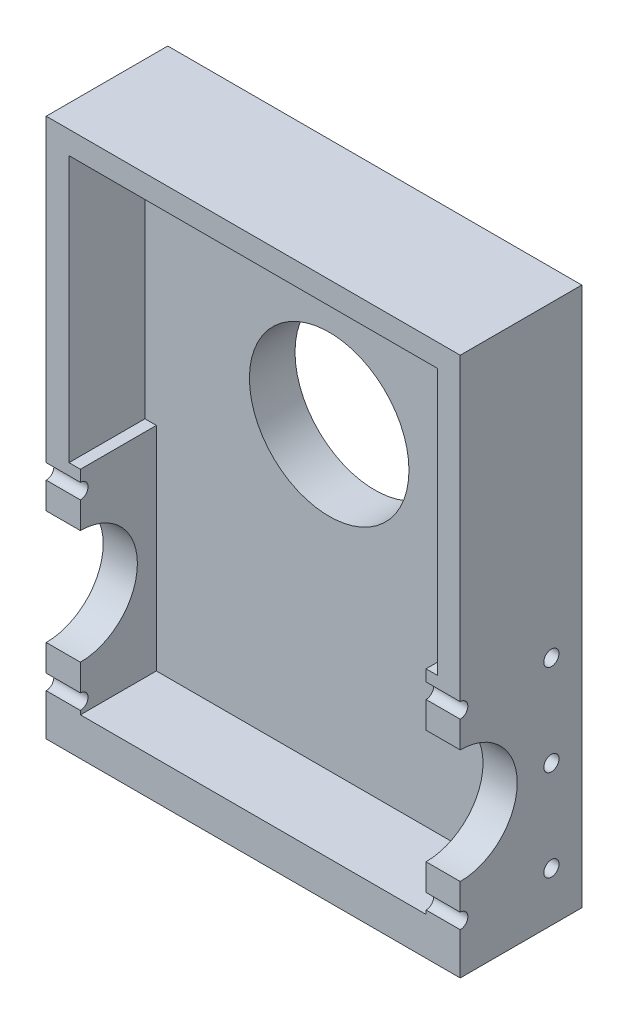
SolidWorks part; units mm, degrees
ref_plane "Front Plane" through (0, 0, 0) normal (0, 0, 1) x (1, 0, 0)
ref_plane "Top Plane" through (0, 0, 0) normal (0, 1, 0) x (1, 0, 0)
ref_plane "Right Plane" through (0, 0, 0) normal (1, 0, 0) x (0, 0, -1)
sketch "Sketch1" plane through (0, 0, 0) normal (0, 0, 1) x (1, 0, 0)
  line L0 (0, 0) -> (0, -52) construction
  line L2 (-48.5, -65) -> (48.5, -65)
  line L3 (-48.5, -65) -> (-48.5, 65)
  line L4 (-48.5, 65) -> (48.5, 65)
  line L5 (48.5, -65) -> (48.5, 65)
  line L6 (-48.5, -65) -> (48.5, 65) construction
  line L7 (-48.5, 65) -> (48.5, -65) construction
  dimension "D1" = 52
  dimension "D2" = 130
  dimension "D3" = 97
extrude "Boss-Extrude1" add sketch "Sketch1" along normal blind 12
sketch "Sketch8" plane through (0, 0, 12) normal (0, 0, 1) x (1, 0, 0)
  line L0 (0, 65) -> (0, 18) construction
  line L1 (48.5, 65) -> (-48.5, 65) construction
  circle A0 centre (0, 18) radius 43.5
  dimension "D2" = 87
  dimension "D1" = 47
sketch "Sketch9" plane through (0, 0, 12) normal (0, 0, 1) x (1, 0, 0)
  circle A0 centre (0, 18) radius 32
  point P19 (8.6603, 13)
  point P21 (0, 18)
  dimension "D1" = 64
extrude "Cut-Extrude2" cut sketch "Sketch9" against normal blind 12
sketch "Sketch11" plane through (0, 0, 0) normal (0, 0, 1) x (1, 0, 0)
  line L0 (-54.5, 71) -> (54.5, 71)
  line L1 (-48.5, -65) -> (48.5, -65)
  line L2 (-48.5, -65) -> (-48.5, 65)
  line L3 (-48.5, 65) -> (48.5, 65)
  line L4 (48.5, -65) -> (48.5, 65)
  line L5 (-48.5, -65) -> (48.5, 65) construction
  line L6 (-48.5, 65) -> (48.5, -65) construction
  line L7 (54.5, -71) -> (54.5, 71)
  line L8 (-54.5, -71) -> (54.5, -71)
  line L9 (-54.5, -71) -> (-54.5, 71)
  point P0 (0, 0)
  dimension "D1" = 6
extrude "Boss-Extrude4" add sketch "Sketch11" along normal blind 32
sketch "Sketch14" plane through (-54.5, 0, 0) normal (-1, 0, 0) x (0, 0, 1)
  line L0 (32, 71) -> (32, -71) construction
  line L1 (32, -71) -> (0, -71) construction
  circle A0 centre (32, -34) radius 15
  point P20 (32, -34)
  point P21 (34.6699, -46.5)
  point P22 (35.5, -27.9378)
  dimension "D1" = 30
  dimension "D2" = 37
sketch "Sketch18" plane through (-48.5, 0, 0) normal (1, 0, 0) x (0, 0, -1)
  line L0 (-12, 65) -> (-12, -65) construction
  line L1 (-32, -65) -> (-12, -65)
  line L2 (-32, -65) -> (-32, -5)
  line L3 (-32, -5) -> (-12, -5)
  line L4 (-12, -65) -> (-12, -5)
  dimension "D1" = 60
extrude "Boss-Extrude5" add sketch "Sketch18" along normal blind 3
mirror "Mirror1" about plane through (0, 0, 0) normal (1, 0, 0) of "Boss-Extrude5"
extrude "Cut-Extrude5" cut sketch "Sketch14" against normal through all
sketch "Sketch20" plane through (0, -65, 0) normal (0, 1, 0) x (1, 0, 0)
  line L1 (-45.5, -12) -> (45.5, -12)
  line L2 (-45.5, -12) -> (-45.5, -32)
  line L3 (-45.5, -32) -> (45.5, -32)
  line L4 (45.5, -12) -> (45.5, -32)
extrude "Boss-Extrude6" add sketch "Sketch20" along normal blind 4
sketch "Sketch21" plane through (-54.5, 0, 0) normal (-1, 0, 0) x (0, 0, 1)
  line L0 (32, -34) -> (32, -10) construction
  line L1 (32, 71) -> (32, -19) construction
  line L2 (0, -34) -> (64.9981, -34) construction
  line L3 (0, 71) -> (0, -71) construction
  circle A0 centre (32, -10) radius 2
  circle A1 centre (8, -10) radius 2
  circle A2 centre (56, -10) radius 2
  circle A3 centre (56, -58) radius 2
  circle A4 centre (32, -58) radius 2
  circle A5 centre (8, -58) radius 2
  circle A6 centre (8, -34) radius 2
  dimension "D2" = 4
  dimension "D3" = 4
  dimension "D4" = 24
  dimension "D5" = 4
  dimension "D6" = 24
  dimension "D7" = 4
  dimension "D1" = 24
extrude "Cut-Extrude6" cut sketch "Sketch21" against normal blind 9
mirror "Mirror2" about plane through (0, 0, 0) normal (1, 0, 0) of "Cut-Extrude6"
sketch "Sketch22" plane through (0, 0, 12) normal (0, 0, 1) x (1, 0, 0)
  circle A0 centre (0, 18) radius 32
  circle A1 centre (0, 18) radius 35
  dimension "D1" = 64
  dimension "D2" = 70
sketch "Sketch23" plane through (0, 0, 0) normal (0, 0, -1) x (-1, 0, 0)
  line L0 (0, 50) -> (0, 56) construction
  line L1 (0, 65) -> (0, 18) construction
  circle A0 centre (0, 18) radius 32 construction
  circle A1 centre (0, 56) radius 2
  circle A2 centre (32.909, 37) radius 2
  circle A3 centre (32.909, -1) radius 2
  circle A4 centre (0, -20) radius 2
  circle A5 centre (-32.909, -1) radius 2
  circle A6 centre (-32.909, 37) radius 2
  point P20 (0, 18)
  dimension "D2" = 4
  dimension "D1" = 6
  dimension "D3" = 6
extrude "Cut-Extrude7" cut sketch "Sketch23" against normal blind 6
sketch "Sketch24" plane through (0, 0, 12) normal (0, 0, 1) x (1, 0, 0)
  circle A0 centre (0, 18) radius 32
sketch "Sketch26" plane through (0, 0, 0) normal (0, 0, -1) x (-1, 0, 0)
  circle A0 centre (0, 18) radius 21
  circle A1 centre (0, 18) radius 32
  dimension "D1" = 42
  dimension "D2" = 64
extrude "Boss-Extrude7" add sketch "Sketch26" against normal blind 12
